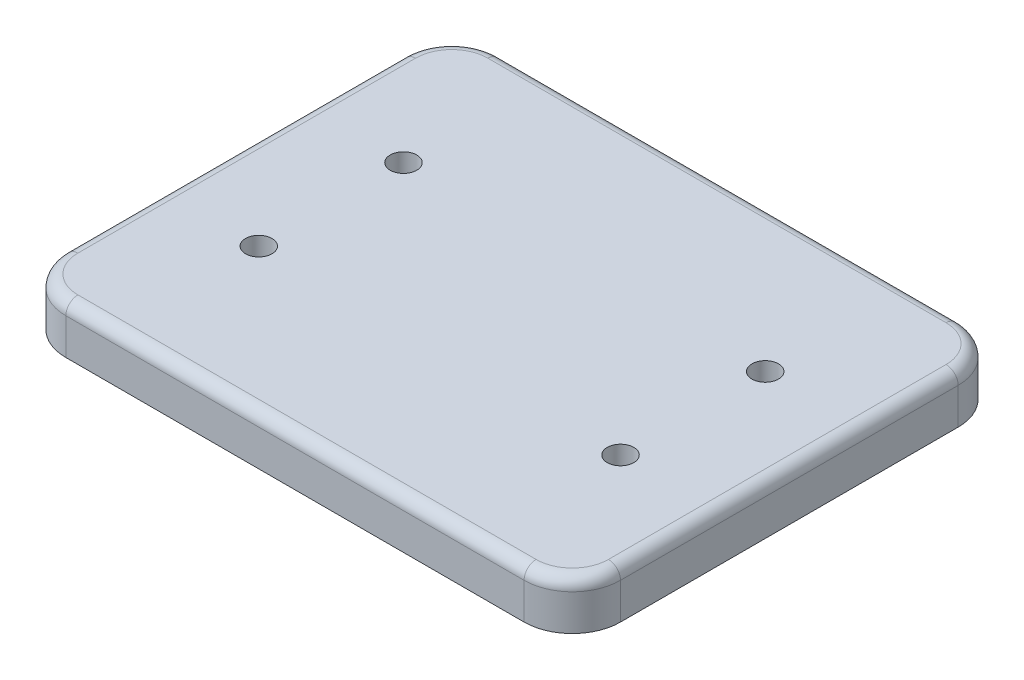
SolidWorks part; units mm, degrees
ref_plane "Front Plane" through (0, 0, 0) normal (0, 0, 1) x (1, 0, 0)
ref_plane "Top Plane" through (0, 0, 0) normal (0, 1, 0) x (1, 0, 0)
ref_plane "Right Plane" through (0, 0, 0) normal (1, 0, 0) x (0, 0, -1)
sketch "Sketch1" plane through (0, 0, 0) normal (0, 1, 0) x (1, 0, 0)
  line L1 (95, -90) -> (-95, -90)
  line L2 (115, -70) -> (115, 70)
  line L3 (95, 90) -> (-95, 90)
  line L4 (-115, -70) -> (-115, 70)
  line L5 (115, -90) -> (-115, 90) construction
  line L6 (115, 90) -> (-115, -90) construction
  arc A0 (-95, -90) -> (-115, -70) centre (-95, -70) cw
  arc A1 (115, 70) -> (95, 90) centre (95, 70) ccw
  arc A2 (95, -90) -> (115, -70) centre (95, -70) ccw
  arc A3 (-95, 90) -> (-115, 70) centre (-95, 70) ccw
  point P0 (0, 0)
  dimension "D3" = 20
  dimension "D1" = 230
  dimension "D2" = 180
extrude "Boss-Extrude1" add sketch "Sketch1" along normal blind 20
fillet "Fillet1" radius 5 8 edges at (-115, 20, 0) (-109.1421, 20, -84.1421) (0, 20, -90) (109.1421, 20, -84.1421) (115, 20, 0) (109.1421, 20, 84.1421) (0, 20, 90) (-109.1421, 20, 84.1421)
sketch "Sketch2" plane through (0, 20, 0) normal (0, 1, 0) x (1, 0, 0)
  circle A0 centre (-75, 30) radius 5.5
  circle A1 centre (75, 30) radius 5.5
  point P7 (0, 0)
  dimension "D4" = 11
  dimension "D1" = 75
  dimension "D2" = 30
  dimension "D3" = 75
extrude "Cut-Extrude1" cut sketch "Sketch2" against normal blind 20
sketch "Sketch3" plane through (0, 0, 0) normal (0, -1, 0) x (1, 0, 0)
  circle A0 centre (-75, -30) radius 9
  circle A1 centre (75, -30) radius 9
  dimension "D1" = 18
extrude "Cut-Extrude2" cut sketch "Sketch3" against normal blind 11
mirror "Mirror1" about plane through (0, 0, 0) normal (0, 0, 1) of "Cut-Extrude2", "Cut-Extrude1"
